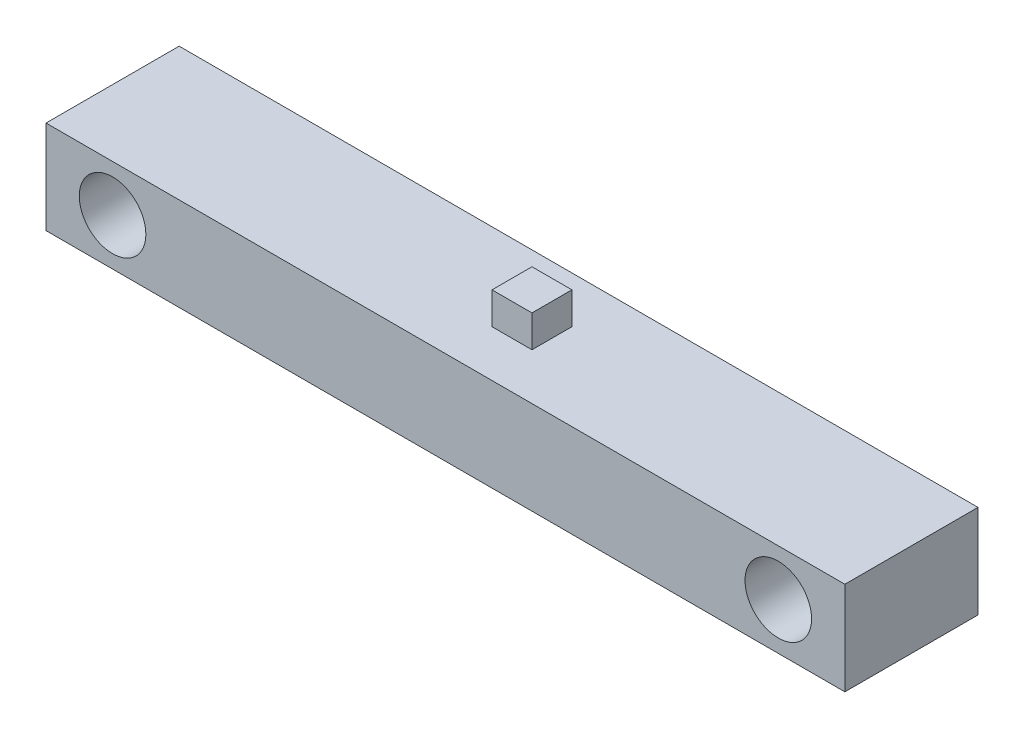
SolidWorks part; units mm, degrees
ref_plane "Front Plane" through (0, 0, 0) normal (0, 0, 1) x (1, 0, 0)
ref_plane "Top Plane" through (0, 0, 0) normal (0, 1, 0) x (1, 0, 0)
ref_plane "Right Plane" through (0, 0, 0) normal (1, 0, 0) x (0, 0, -1)
sketch "Sketch1" plane through (0, 0, 0) normal (0, 1, 0) x (1, 0, 0)
  line L1 (-150, 50) -> (150, 50)
  line L2 (-150, 50) -> (-150, 0)
  line L3 (-150, 0) -> (150, 0)
  line L4 (150, 50) -> (150, 0)
  dimension "D1" = 300
  dimension "D2" = 50
extrude "Boss-Extrude1" add sketch "Sketch1" along normal blind 35
sketch "Sketch2" plane through (0, 35, 0) normal (0, 1, 0) x (1, 0, 0)
  line L0 (150, 50) -> (-150, 50) construction
  line L1 (0, 32.5) -> (15, 32.5)
  line L2 (0, 32.5) -> (0, 17.5)
  line L3 (0, 17.5) -> (15, 17.5)
  line L4 (15, 32.5) -> (15, 17.5)
  line L6 (-150, 50) -> (-150, 0) construction
  dimension "D1" = 15
  dimension "D2" = 15
  dimension "D3" = 17.5
  dimension "D4" = 150
extrude "Boss-Extrude2" add sketch "Sketch2" along normal blind 12
sketch "Sketch3" plane through (0, 0, 0) normal (0, 0, 1) x (1, 0, 0)
  line L3 (-150, 35) -> (150, 35) construction
  circle A1 centre (-125, 17.5) radius 12.5
  circle A2 centre (125, 17.5) radius 12.5
  dimension "D2" = 250
  dimension "D1" = 25
  dimension "D5" = 25
  dimension "D3" = 125
  dimension "D4" = 17.5
extrude "Cut-Extrude1" cut sketch "Sketch3" against normal up to next
